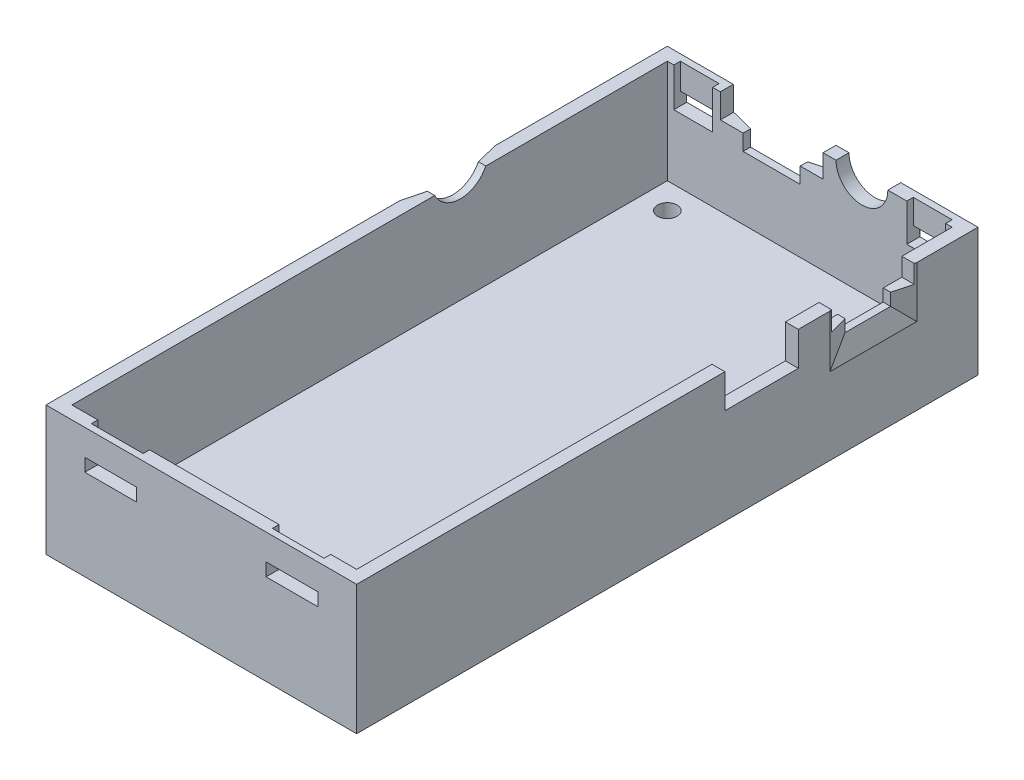
SolidWorks part; units mm, degrees
ref_plane "Front Plane" through (0, 0, 0) normal (0, 0, 1) x (1, 0, 0)
ref_plane "Top Plane" through (0, 0, 0) normal (0, 1, 0) x (1, 0, 0)
ref_plane "Right Plane" through (0, 0, 0) normal (1, 0, 0) x (0, 0, -1)
sketch "Sketch1" plane through (0, 0, 0) normal (0, 1, 0) x (1, 0, 0)
  line L1 (0, 0) -> (-38.1, 0)
  line L2 (0, 0) -> (0, -76.2)
  line L3 (0, -76.2) -> (-38.1, -76.2)
  line L4 (-38.1, 0) -> (-38.1, -76.2)
  dimension "D1" = 38.1
  dimension "D2" = 76.2
extrude "Boss-Extrude1" add sketch "Sketch1" along normal blind 25.4
sketch "Sketch2" plane through (0, 0, 0) normal (0, 1, 0) x (1, 0, 0)
  line L1 (-33.3375, -4.7625) -> (-4.7625, -4.7625) construction
  line L2 (-33.3375, -4.7625) -> (-33.3375, -71.4375) construction
  line L3 (-33.3375, -71.4375) -> (-4.7625, -71.4375) construction
  line L4 (-4.7625, -4.7625) -> (-4.7625, -71.4375) construction
  line L9 (-33.3375, -38.1) -> (-38.1, -38.1) construction
  line L10 (-38.1, 0) -> (-38.1, -76.2) construction
  line L11 (-4.7625, -38.1) -> (0, -38.1) construction
  line L12 (0, -76.2) -> (0, 0) construction
  line L13 (-19.05, -71.4375) -> (-19.05, -76.2) construction
  line L14 (-38.1, -76.2) -> (0, -76.2) construction
  line L15 (-19.05, -4.7625) -> (-19.05, 0) construction
  line L16 (0, 0) -> (-38.1, 0) construction
  circle A0 centre (-33.3375, -4.7625) radius 1.2
  circle A1 centre (-4.7625, -4.7625) radius 1.2
  circle A2 centre (-33.3375, -71.4375) radius 1.2
  circle A3 centre (-4.7625, -71.4375) radius 1.2
  dimension "D5" = 2.4
  dimension "D1" = 28.575
  dimension "D2" = 66.675
extrude "Cut-Extrude1" cut sketch "Sketch2" along normal blind 3.175
sketch "Sketch4" plane through (0, 25.4, 0) normal (0, 1, 0) x (1, 0, 0)
  line L0 (0, 0) -> (-38.1, 0) construction
  line L1 (-36.5125, -1.5875) -> (-1.5875, -1.5875)
  line L2 (-36.5125, -1.5875) -> (-36.5125, -74.6125)
  line L3 (-36.5125, -74.6125) -> (-1.5875, -74.6125)
  line L4 (-1.5875, -1.5875) -> (-1.5875, -74.6125)
  line L5 (-38.1, 0) -> (-38.1, -76.2) construction
  line L6 (-38.1, -76.2) -> (0, -76.2) construction
  line L7 (0, -76.2) -> (0, 0) construction
  dimension "D1" = 1.5875
  dimension "D2" = 1.5875
  dimension "D3" = 1.5875
  dimension "D4" = 1.5875
extrude "Cut-Extrude2" cut sketch "Sketch4" against normal blind 22.225
sketch "Sketch5" plane through (-38.1, 0, 0) normal (-1, 0, 0) x (0, 0, 1)
  line L0 (76.2, 15.875) -> (30.1152, 15.875)
  line L1 (76.2, 25.4) -> (76.2, 0) construction
  line L2 (0, 25.4) -> (0, 0) construction
  line L3 (0, 15.875) -> (0, 25.4)
  line L4 (0, 25.4) -> (76.2, 25.4)
  line L5 (76.2, 25.4) -> (76.2, 15.875)
  line L6 (23.8514, 15.875) -> (0, 15.875)
  arc A0 (23.8514, 15.875) -> (30.1152, 15.875) centre (26.9833, 17.4375) ccw
  dimension "D2" = 7
  dimension "D1" = 9.525
extrude "Cut-Extrude3" cut sketch "Sketch5" against normal blind 1.5875
sketch "Sketch6" plane through (0, 0, 0) normal (0, 0, -1) x (-1, 0, 0)
  line L0 (30.0117, 12.8875) -> (30.0117, 15.875)
  line L1 (30.0117, 15.875) -> (36.5125, 15.875)
  line L2 (1.5875, 10.9375) -> (36.5125, 10.9375) construction
  line L3 (27.2117, 10.9375) -> (20.2117, 10.9375)
  line L4 (36.5125, 3.175) -> (36.5125, 15.875) construction
  line L5 (15.8217, 15.7025) -> (17.4117, 15.7025)
  line L6 (9.4717, 15.7025) -> (1.5875, 15.7025)
  line L7 (1.5875, 10.9375) -> (1.5875, 23.5375) construction
  line L8 (36.5125, 15.875) -> (36.5125, 25.4)
  line L9 (36.5125, 25.4) -> (1.5875, 25.4)
  line L10 (1.5875, 25.4) -> (1.5875, 15.7025)
  line L11 (20.2117, 10.9375) -> (20.2117, 12.8875)
  line L12 (20.2117, 12.8875) -> (17.4117, 12.8875)
  line L13 (17.4117, 12.8875) -> (17.4117, 15.7025)
  line L14 (36.5125, 15.875) -> (38.1, 15.875) construction
  line L15 (30.0117, 12.8875) -> (27.2117, 12.8875)
  line L16 (27.2117, 12.8875) -> (27.2117, 10.9375)
  line L18 (17.4117, 14.8375) -> (17.4117, 10.9375) construction
  line L19 (30.0117, 14.8375) -> (30.0117, 10.9375) construction
  arc A1 (9.4717, 15.7025) -> (15.8217, 15.7025) centre (12.6467, 15.7025) ccw
  circle A2 centre (12.6467, 15.7025) radius 3.175 construction
  dimension "D1" = 7
extrude "Cut-Extrude4" cut sketch "Sketch6" against normal blind 1.5875
sketch "Sketch7" plane through (0, 0, 76.2) normal (0, 0, 1) x (1, 0, 0)
  line L0 (-36.5125, 15.875) -> (-1.5875, 15.875)
  line L1 (-1.5875, 3.175) -> (-1.5875, 25.4) construction
  line L2 (-1.5875, 15.875) -> (-1.5875, 25.4)
  line L3 (-1.5875, 25.4) -> (-36.5125, 25.4)
  line L4 (-36.5125, 25.4) -> (-36.5125, 15.875)
extrude "Cut-Extrude5" cut sketch "Sketch7" against normal blind 1.5875
sketch "Sketch8" plane through (0, 0, 0) normal (1, 0, 0) x (0, 0, -1)
  line L0 (-76.2, 15.875) -> (-31.0375, 15.875)
  line L1 (-17.9131, 15.875) -> (-17.9131, 13.4775)
  line L2 (-17.9131, 13.4775) -> (-15.6331, 13.4775)
  line L3 (-15.6331, 12.1775) -> (-15.6331, 14.7775) construction
  line L4 (-15.6331, 13.4775) -> (-15.6281, 11.9775)
  line L5 (-15.6281, 11.9775) -> (-10.0381, 11.9775)
  line L6 (-10.0381, 11.9775) -> (-10.0331, 13.4775)
  line L7 (-10.0331, 14.7775) -> (-10.0331, 12.1775) construction
  line L8 (-10.0331, 13.4775) -> (-7.7531, 13.4775)
  line L9 (-17.9131, 15.3675) -> (-17.9131, 11.5875) construction
  line L11 (-74.6125, 15.875) -> (-76.2, 15.875) construction
  line L13 (0, 15.875) -> (0, 25.4)
  line L14 (0, 25.4) -> (-76.2, 25.4)
  line L15 (-76.2, 25.4) -> (-76.2, 15.875)
  line L16 (0, 25.4) -> (0, 0) construction
  line L18 (0, 15.7025) -> (-7.7531, 15.7025)
  line L19 (-7.7531, 15.7025) -> (-7.7531, 13.4775)
  line L20 (-7.7531, 11.5875) -> (-7.7531, 15.3675) construction
  line L21 (-31.0375, 15.875) -> (-31.0375, 11.7312)
  line L22 (-31.0375, 10.9375) -> (-31.0375, 23.5375) construction
  line L23 (-22.0375, 11.7312) -> (-31.0375, 11.7312)
  line L25 (-17.9131, 15.875) -> (-22.0375, 15.875)
  line L26 (-22.0375, 10.9375) -> (-22.0375, 23.5375) construction
  line L29 (-1.5875, 15.875) -> (-23.8514, 15.875) construction
  line L30 (-22.0375, 15.875) -> (-22.0375, 11.7312)
  line L31 (-33.3375, 10.9375) -> (-1.5875, 10.9375) construction
  line M1 (0, 0) -> (0, 25.4)
  line M4 (0, 25.4) -> (-76.2, 25.4)
  line M5 (-76.2, 25.4) -> (-76.2, 0)
  dimension "D1" = 0.7937
extrude "Cut-Extrude6" cut sketch "Sketch8" against normal blind 1.5875 contours L19 L18 L0 L1 L2 L4 L5 L6 L8 M1 M4 M5
chamfer "Chamfer1" distance 2.54 angle 15 1 edges at (-38.1, 13.9375, 26.9833)
chamfer "Chamfer3" distance 2.54 angle 15 3 edges at (-27.2117, 11.9125, 0) (-20.2117, 11.9125, 0) (-23.7117, 10.9375, 0)
chamfer "Chamfer4" distance 2.54 angle 15 3 edges at (0, 12.7275, 10.0356) (0, 12.7275, 15.6306) (0, 11.9775, 12.8331)
sketch "Sketch10" plane through (0, 15.875, 0) normal (0, 1, 0) x (1, 0, 0)
  line L0 (-33.3375, -74.6125) -> (-33.3375, -75.4062)
  line L1 (-36.5125, -74.6125) -> (-1.5875, -74.6125) construction
  line L2 (-33.3375, -75.4062) -> (-26.9875, -75.4062)
  line L3 (-26.9875, -75.4062) -> (-26.9875, -74.6125)
  line L4 (-36.5125, -30.1152) -> (-36.5125, -74.6125) construction
  line L5 (-4.7625, -74.6125) -> (-4.7625, -75.4355)
  line L6 (-4.7625, -75.4355) -> (-11.1125, -75.4355)
  line L7 (-11.1125, -75.4355) -> (-11.1125, -74.6125)
  line L8 (-11.1125, -74.6125) -> (-4.7625, -74.6125)
  line L9 (-1.5875, -74.6125) -> (-1.5875, -31.0375) construction
  line L11 (-35.7188, -1.5875) -> (-30.9563, -1.5875)
  line L12 (-35.7188, -1.5875) -> (-35.7188, -0.7938)
  line L13 (-35.7188, -0.7938) -> (-30.9563, -0.7938)
  line L14 (-30.9563, -1.5875) -> (-30.9563, -0.7938)
  line L17 (-2.3812, -1.5875) -> (-7.1437, -1.5875)
  line L18 (-2.3812, -1.5875) -> (-2.3812, -0.7938)
  line L19 (-2.3812, -0.7938) -> (-7.1437, -0.7938)
  line L20 (-7.1437, -1.5875) -> (-7.1437, -0.7938)
  line L22 (-36.5125, -1.5875) -> (-36.5125, -23.8514) construction
  line L23 (-1.5875, -1.5875) -> (-1.5875, -7.7531) construction
  line L24 (-1.5875, -1.5875) -> (-9.4717, -1.5875) construction
  line L25 (-30.0117, -1.5875) -> (-36.5125, -1.5875) construction
  line M10 (-1.5875, -74.6125) -> (-36.5125, -74.6125)
  dimension "D1" = 0.7937
  dimension "D2" = 3.175
  dimension "D3" = 6.35
  dimension "D4" = 6.35
  dimension "D5" = 3.175
  dimension "D6" = 4.7625
  dimension "D7" = 0.7937
  dimension "D8" = 0.7937
  dimension "D9" = 4.7625
  dimension "D10" = 0.7937
  dimension "D11" = 0.7937
extrude "Cut-Extrude7" cut sketch "Sketch10" against normal blind 4.7625 contours L2 L3 L0 M10 | L11 L14 L13 L12 | L20 L17 L18 L19 | L8 L5 L6 L7
sketch "Sketch11" plane through (0, 0, 76.2) normal (0, 0, 1) x (1, 0, 0)
  line L0 (-33.3375, 11.1125) -> (-33.3375, 12.7)
  line L2 (-33.3375, 12.7) -> (-26.9875, 12.7)
  line L4 (-26.9875, 12.7) -> (-26.9875, 11.1125)
  line L5 (-26.9875, 11.1125) -> (-33.3375, 11.1125)
  line L6 (-33.3375, 11.1125) -> (-26.9875, 11.1125) construction
  line L7 (-33.3375, 11.1125) -> (-33.3375, 15.875) construction
  line L8 (-26.9875, 11.1125) -> (-26.9875, 15.875) construction
  line L9 (-4.7625, 11.1125) -> (-4.7625, 15.875) construction
  line L10 (-11.1125, 11.1125) -> (-4.7625, 11.1125)
  line L11 (-11.1125, 11.1125) -> (-11.1125, 12.7)
  line L12 (-11.1125, 12.7) -> (-4.7625, 12.7)
  line L13 (-4.7625, 11.1125) -> (-4.7625, 12.7)
  dimension "D1" = 1.5875
  dimension "D2" = 1.5875
extrude "Cut-Extrude8" cut sketch "Sketch11" against normal up to next
sketch "Sketch14" plane through (0, 0, 0) normal (0, 0, -1) x (-1, 0, 0)
  line L0 (30.9563, 11.1125) -> (30.9563, 15.875) construction
  line L1 (35.7188, 11.1125) -> (30.9563, 11.1125)
  line L2 (35.7188, 11.1125) -> (35.7188, 12.7)
  line L3 (35.7188, 12.7) -> (30.9563, 12.7)
  line L4 (30.9563, 11.1125) -> (30.9563, 12.7)
  line L5 (7.1437, 11.1125) -> (7.1437, 15.7025) construction
  line L6 (2.3812, 11.1125) -> (7.1437, 11.1125)
  line L7 (2.3812, 11.1125) -> (2.3812, 12.7)
  line L8 (2.3812, 12.7) -> (7.1437, 12.7)
  line L9 (7.1437, 11.1125) -> (7.1437, 12.7)
  dimension "D1" = 1.5875
  dimension "D2" = 1.5875
extrude "Cut-Extrude9" cut sketch "Sketch14" against normal blind 1.5875
